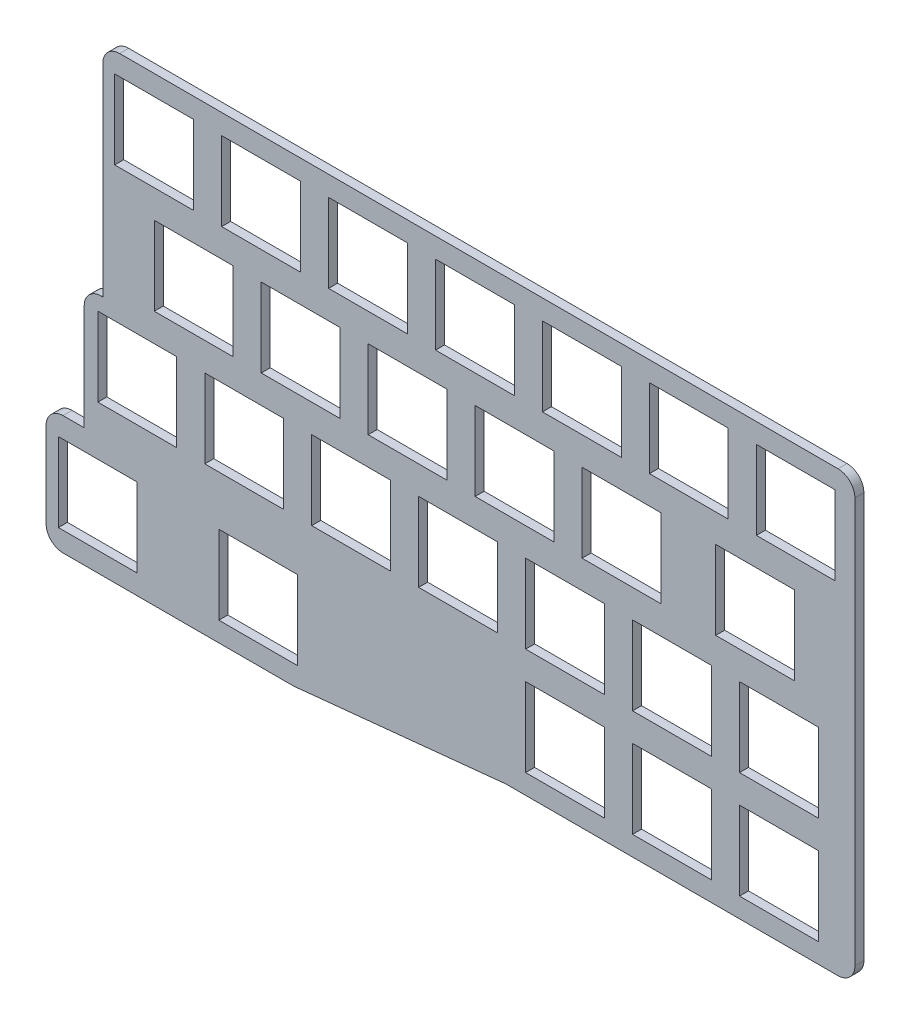
SolidWorks part; units mm, degrees
ref_plane "Front Plane" through (0, 0, 0) normal (0, 0, 1) x (1, 0, 0)
ref_plane "Top Plane" through (0, 0, 0) normal (0, 1, 0) x (1, 0, 0)
ref_plane "Right Plane" through (0, 0, 0) normal (1, 0, 0) x (0, 0, -1)
sketch "Sketch1" plane through (0, 0, 0) normal (0, 0, 1) x (1, 0, 0)
  line B0 (-78.751, 0.6419) -> (-78.751, 47.5532)
  line B1 (60.999, -10.045) -> (60.999, -24.045)
  line B2 (-53.001, -5.045) -> (-39.001, -5.045)
  line B3 (-75.7491, 50.5532) -> (78.5009, 50.4569)
  arc B4 (81.499, 47.4569) -> (78.5009, 50.4569) centre (78.499, 47.4569) ccw
  line B5 (81.499, 47.4569) -> (81.499, -24.545)
  arc B6 (78.499, -27.545) -> (81.499, -24.545) centre (78.499, -24.545) ccw
  line B7 (78.499, -27.545) -> (19.6498, -27.545)
  arc B8 (19.6498, -27.545) -> (19.349, -27.5601) centre (19.6498, -30.545) ccw
  line B9 (19.349, -27.5601) -> (-18.0509, -31.3298)
  arc B10 (-18.3518, -31.345) -> (-18.0509, -31.3298) centre (-18.3518, -28.345) ccw
  line B11 (-18.3518, -31.345) -> (-66.0887, -31.345)
  arc B12 (-68.9347, -29.2936) -> (-66.0887, -31.345) centre (-66.0887, -28.345) ccw
  line B13 (-68.9347, -29.2936) -> (-78.597, -0.3068)
  arc B14 (-78.751, 0.6419) -> (-78.597, -0.3068) centre (-75.751, 0.6419) ccw
  arc B15 (-75.7491, 50.5532) -> (-78.751, 47.5532) centre (-75.751, 47.5532) ccw
  line B16 (-50.001, 32.955) -> (-36.001, 32.955)
  line B17 (-36.001, 32.955) -> (-36.001, 46.955)
  line B18 (-36.001, 46.955) -> (-50.001, 46.955)
  line B19 (-50.001, 46.955) -> (-50.001, 32.955)
  line B20 (-31.001, 32.955) -> (-17.001, 32.955)
  line B21 (-17.001, 32.955) -> (-17.001, 46.955)
  line B22 (-17.001, 46.955) -> (-31.001, 46.955)
  line B23 (-31.001, 46.955) -> (-31.001, 32.955)
  line B24 (-12.001, 32.955) -> (1.999, 32.955)
  line B25 (1.999, 32.955) -> (1.999, 46.955)
  line B26 (1.999, 46.955) -> (-12.001, 46.955)
  line B27 (-12.001, 46.955) -> (-12.001, 32.955)
  line B28 (6.999, 32.955) -> (20.999, 32.955)
  line B29 (20.999, 32.955) -> (20.999, 46.955)
  line B30 (20.999, 46.955) -> (6.999, 46.955)
  line B31 (6.999, 46.955) -> (6.999, 32.955)
  line B32 (25.999, 32.955) -> (39.999, 32.955)
  line B33 (39.999, 32.955) -> (39.999, 46.955)
  line B34 (39.999, 46.955) -> (25.999, 46.955)
  line B35 (25.999, 46.955) -> (25.999, 32.955)
  line B36 (44.999, 32.955) -> (58.999, 32.955)
  line B37 (58.999, 32.955) -> (58.999, 46.955)
  line B38 (58.999, 46.955) -> (44.999, 46.955)
  line B39 (44.999, 46.955) -> (44.999, 32.955)
  line B40 (63.999, 32.955) -> (77.999, 32.955)
  line B41 (77.999, 32.955) -> (77.999, 46.955)
  line B42 (77.999, 46.955) -> (63.999, 46.955)
  line B43 (63.999, 46.955) -> (63.999, 32.955)
  line B44 (-42.971, 13.955) -> (-28.971, 13.955)
  line B45 (-28.971, 13.955) -> (-28.971, 27.955)
  line B46 (-28.971, 27.955) -> (-42.971, 27.955)
  line B47 (-42.971, 27.955) -> (-42.971, 13.955)
  line B48 (-23.971, 13.955) -> (-9.971, 13.955)
  line B49 (-9.971, 13.955) -> (-9.971, 27.955)
  line B50 (-9.971, 27.955) -> (-23.971, 27.955)
  line B51 (-23.971, 27.955) -> (-23.971, 13.955)
  line B52 (-4.971, 13.955) -> (9.029, 13.955)
  line B53 (9.029, 13.955) -> (9.029, 27.955)
  line B54 (9.029, 27.955) -> (-4.971, 27.955)
  line B55 (-4.971, 27.955) -> (-4.971, 13.955)
  line B56 (14.029, 13.955) -> (28.029, 13.955)
  line B57 (28.029, 13.955) -> (28.029, 27.955)
  line B58 (28.029, 27.955) -> (14.029, 27.955)
  line B59 (14.029, 27.955) -> (14.029, 13.955)
  line B60 (33.029, 13.955) -> (47.029, 13.955)
  line B61 (47.029, 13.955) -> (47.029, 27.955)
  line B62 (47.029, 27.955) -> (33.029, 27.955)
  line B63 (33.029, 27.955) -> (33.029, 13.955)
  line B64 (56.779, 13.955) -> (70.779, 13.955)
  line B65 (70.779, 13.955) -> (70.779, 27.955)
  line B66 (70.779, 27.955) -> (56.779, 27.955)
  line B67 (56.779, 27.955) -> (56.779, 13.955)
  line B68 (-39.001, -5.045) -> (-39.001, 8.955)
  line B69 (-39.001, 8.955) -> (-53.001, 8.955)
  line B70 (-53.001, 8.955) -> (-53.001, -5.045)
  line B71 (-34.001, -5.045) -> (-20.001, -5.045)
  line B72 (-20.001, -5.045) -> (-20.001, 8.955)
  line B73 (-20.001, 8.955) -> (-34.001, 8.955)
  line B74 (-34.001, 8.955) -> (-34.001, -5.045)
  line B75 (-15.001, -5.045) -> (-1.001, -5.045)
  line B76 (-1.001, -5.045) -> (-1.001, 8.955)
  line B77 (-1.001, 8.955) -> (-15.001, 8.955)
  line B78 (-15.001, 8.955) -> (-15.001, -5.045)
  line B79 (3.999, -5.045) -> (17.999, -5.045)
  line B80 (17.999, -5.045) -> (17.999, 8.955)
  line B81 (17.999, 8.955) -> (3.999, 8.955)
  line B82 (3.999, 8.955) -> (3.999, -5.045)
  line B83 (22.999, -5.045) -> (36.999, -5.045)
  line B84 (36.999, -5.045) -> (36.999, 8.955)
  line B85 (36.999, 8.955) -> (22.999, 8.955)
  line B86 (22.999, 8.955) -> (22.999, -5.045)
  line B87 (41.999, -5.045) -> (55.999, -5.045)
  line B88 (55.999, -5.045) -> (55.999, 8.955)
  line B89 (55.999, 8.955) -> (41.999, 8.955)
  line B90 (41.999, 8.955) -> (41.999, -5.045)
  line B91 (60.999, -5.045) -> (74.999, -5.045)
  line B92 (74.999, -5.045) -> (74.999, 8.955)
  line B93 (74.999, 8.955) -> (60.999, 8.955)
  line B94 (60.999, 8.955) -> (60.999, -5.045)
  line B95 (22.999, -24.045) -> (36.999, -24.045)
  line B96 (36.999, -24.045) -> (36.999, -10.045)
  line B97 (36.999, -10.045) -> (22.999, -10.045)
  line B98 (22.999, -10.045) -> (22.999, -24.045)
  line B99 (41.999, -24.045) -> (55.999, -24.045)
  line B100 (55.999, -24.045) -> (55.999, -10.045)
  line B101 (55.999, -10.045) -> (41.999, -10.045)
  line B102 (41.999, -10.045) -> (41.999, -24.045)
  line B103 (60.999, -24.045) -> (74.999, -24.045)
  line B104 (74.999, -24.045) -> (74.999, -10.045)
  line B105 (74.999, -10.045) -> (60.999, -10.045)
  line B106 (-60.001, -27.845) -> (-46.001, -27.845)
  line B107 (-46.001, -27.845) -> (-46.001, -13.845)
  line B108 (-46.001, -13.845) -> (-60.001, -13.845)
  line B109 (-60.001, -13.845) -> (-60.001, -27.845)
  line B110 (-31.501, -27.845) -> (-17.501, -27.845)
  line B111 (-17.501, -27.845) -> (-17.501, -13.845)
  line B112 (-17.501, -13.845) -> (-31.501, -13.845)
  line B113 (-31.501, -13.845) -> (-31.501, -27.845)
sketch_block_instance "switch_plate (2)-1"
sketch_block "switch_plate (2)"
extrude "Boss-Extrude1" add sketch "Sketch1" along normal blind 1.6
sketch "Sketch2" plane through (0, 0, 1.6) normal (0, 0, 1) x (1, 0, 0)
  line L0 (-52.114, 52.1964) -> (-52.114, 11.5851)
  line L1 (-52.114, 11.5851) -> (-55.4157, 11.5851)
  line L2 (-55.4157, 11.5851) -> (-55.4157, -10.2063)
  line L3 (-55.4157, -10.2063) -> (-62.1843, -10.2063)
  line L4 (-62.1843, -10.2063) -> (-62.1843, -38.6011)
  line L5 (-62.1843, -38.6011) -> (-84.4709, -34.1438)
  line L6 (-84.4709, -34.1438) -> (-95.2016, 49.8852)
  line L7 (-95.2016, 49.8852) -> (-53.7649, 58.3046)
  line L8 (-53.7649, 58.3046) -> (-52.114, 52.1964)
extrude "Cut-Extrude1" cut sketch "Sketch2" against normal through all
fillet "Fillet1" radius 3 4 edges at (-52.114, 50.5384, 0.8) (-62.1843, -10.2063, 0.8) (-55.4157, 11.5851, 0.8) (-62.1843, -31.345, 0.8)
